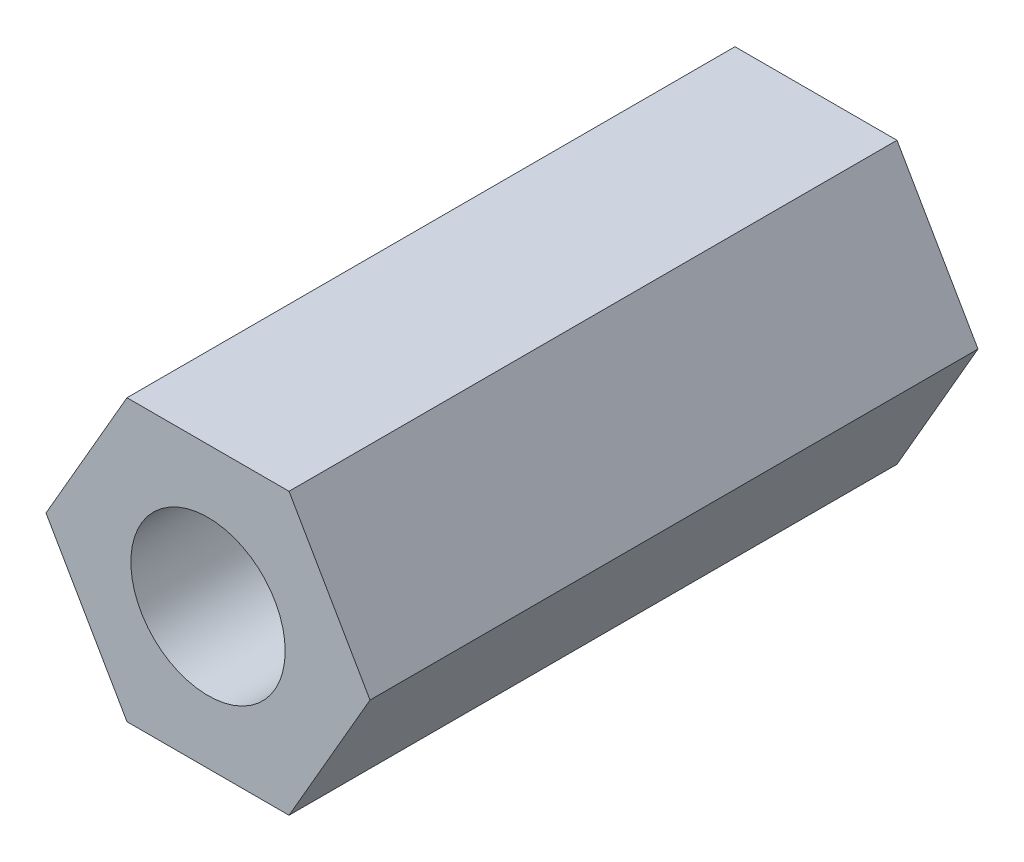
SolidWorks part; units mm, degrees
material "普通碳钢"
ref_plane "前视" through (0, 0, 0) normal (0, 0, 1) x (1, 0, 0)
ref_plane "上视" through (0, 0, 0) normal (0, 1, 0) x (1, 0, 0)
ref_plane "右视" through (0, 0, 0) normal (1, 0, 0) x (0, 0, -1)
sketch "草图1" plane through (0, 0, 0) normal (0, 0, 1) x (1, 0, 0)
  line L0 (0, 0) -> (3.4641, 0)
  line L1 (3.4641, 0) -> (5.1962, -3)
  line L2 (5.1962, -3) -> (3.4641, -6)
  line L3 (3.4641, -6) -> (0, -6)
  line L4 (0, -6) -> (-1.7321, -3)
  line L5 (-1.7321, -3) -> (0, 0)
  dimension "D1" = 6
  dimension "D2" = 6
extrude "凸台-拉伸1" add sketch "草图1" along normal blind 13
hole_wizard "M4 螺纹孔1" positions "草图3" profile "草图2" tap size "M4" standard "GB" end condition through all
sketch "草图3" plane through (0, 0, 13) normal (0, 0, 1) x (1, 0, 0)
  line L0 (-1.7321, -3) -> (5.1962, -3) construction
  line L2 (1.7321, 0) -> (1.7321, -6) construction
  line L3 (3.4641, 0) -> (0, 0) construction
  line L4 (0, -6) -> (3.4641, -6) construction
  point P0 (1.7321, -3)
cosmetic thread "孔螺蚊线1"
sketch "草图2" plane through (1.7321, -3, 13) normal (1, 0, 0) x (0, -1, 0)
  line L0 (0, 0) -> (0, 13)
  line L1 (0, 13) -> (1.65, 13)
  line L2 (1.65, 13) -> (1.65, 0)
  line L5 (1.65, 0) -> (0, 0)
  line L11 (0, -6.35) -> (0, 107.95) construction
  dimension "通孔螺纹孔钻头直径" = 3.3
  dimension "通孔螺纹孔钻头深度" = 13
